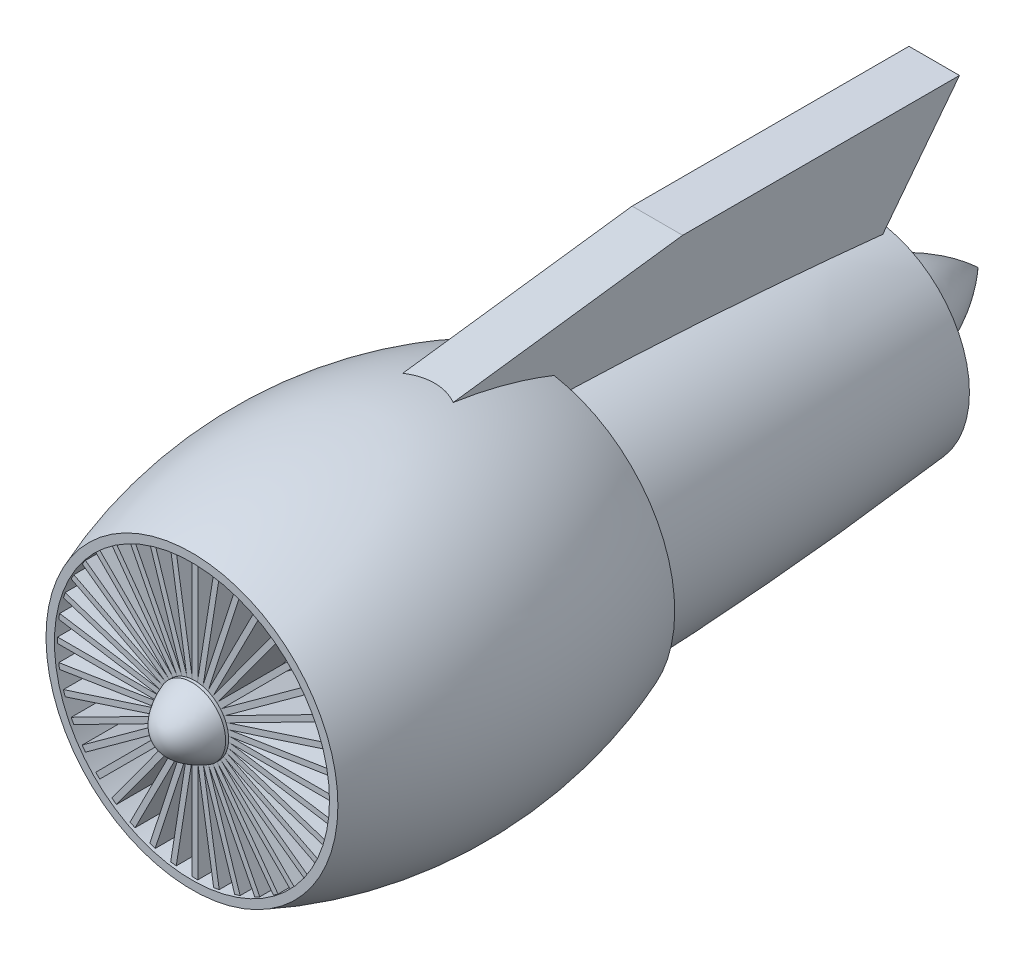
SolidWorks part; units mm, degrees
ref_plane "Front Plane" through (0, 0, 0) normal (0, 0, 1) x (1, 0, 0)
ref_plane "Top Plane" through (0, 0, 0) normal (0, 1, 0) x (1, 0, 0)
ref_plane "Right Plane" through (0, 0, 0) normal (1, 0, 0) x (0, 0, -1)
sketch "Sketch2" plane through (0, 0, 0) normal (1, 0, 0) x (0, 0, -1)
  line L0 (0, 0) -> (7418.07, 0) construction
  line L1 (304.8, 0) -> (304.8, 1320.8)
  line L2 (0, 1606.55) -> (7418.07, 1606.55) construction
  line L3 (0, 1606.55) -> (0, -1606.55) construction
  line L4 (0, -1606.55) -> (7418.07, -1606.55) construction
  line L5 (7418.07, 1606.55) -> (7418.07, -1606.55) construction
  line L6 (3352.8, 0) -> (3352.8, 1320.8)
  line L7 (6400.8, 0) -> (6400.8, 939.8)
  line L8 (0, 0) -> (7418.07, 0)
  arc A0 (304.8, 1320.8) -> (3352.8, 1320.8) centre (1828.8, -2600.325) cw
  arc A1 (3352.8, 1143) -> (6400.8, 939.8) centre (2010.8023, -41948.565) cw
  arc A2 (6400.8, 469.9) -> (7418.07, 0) centre (6186.9994, -1329.0255) cw
  spline S0 degree 3 poles (304.8, 304.8) (224.0091, 277.1634) (0, 180.4453) (0, 0) knots 0 0 0 0 1 1 1 1
  point P7 (0, 0)
  dimension "D10" = 43112.4568
  dimension "D11" = 1811.586
  dimension "D1" = 7418.07
  dimension "D2" = 3213.1
  dimension "D3" = 304.8
  dimension "D4" = 304.8
  dimension "D5" = 1320.8
  dimension "D6" = 3048
  dimension "D7" = 3048
  dimension "D8" = 177.8
  dimension "D9" = 203.2
revolve "Revolve3" add sketch "Sketch2" angle 360 about L0
sketch "Sketch3" plane through (0, 0, -304.8) normal (0, 0, 1) x (1, 0, 0)
  circle A0 centre (0, 0) radius 1244.6
  circle A1 centre (0, 0) radius 304.8
  circle A2 centre (0, 0) radius 304.8 construction
  circle A3 centre (0, 0) radius 1320.8 construction
  dimension "D1" = 76.2
extrude "Cut-Extrude1" cut sketch "Sketch3" against normal blind 609.6
sketch "Sketch4" plane through (0, 0, -6400.8) normal (0, 0, -1) x (-1, 0, 0)
  circle A0 centre (0, 0) radius 469.9
  circle A1 centre (0, 0) radius 469.9 construction
  circle A2 centre (0, 0) radius 914.4
  circle A3 centre (0, 0) radius 939.8 construction
  dimension "D1" = 25.4
extrude "Cut-Extrude4" cut sketch "Sketch4" against normal blind 914.4
sketch "Sketch5" plane through (0, 0, 0) normal (1, 0, 0) x (0, 0, -1)
  line L0 (1777.5046, 1457.7467) -> (4516.6379, 1817.1065)
  line L1 (4516.6379, 1817.1065) -> (7021.9455, 1817.1065)
  line L2 (7021.9455, 1817.1065) -> (6300.0388, 883.2967)
  line L3 (6300.0388, 883.2967) -> (3352.8, 1032.7016)
  line L4 (3352.8, -1320.8) -> (3352.8, 1320.8) construction
  line L5 (3352.8, 1032.7016) -> (1777.5046, 1457.7467)
extrude "Boss-Extrude1" add sketch "Sketch5" along normal mid plane 457.2
sketch "Sketch6" plane through (0, 0, -914.4) normal (0, 0, 1) x (1, 0, 0)
  line L0 (0, 0) -> (0, 1320.8) construction
  line L1 (-25.4, 1244.3408) -> (25.4, 1244.3408)
  line L2 (-25.4, 1244.3408) -> (-25.4, 0)
  line L3 (-25.4, 0) -> (25.4, 0)
  line L4 (25.4, 1244.3408) -> (25.4, 0)
  circle A0 centre (0, 0) radius 1244.6 construction
  point P6 (0, 1244.3408)
  dimension "D1" = 50.8
extrude "Boss-Extrude4" add sketch "Sketch6" along normal blind 582.422 separate body
pattern_circular "CirPattern2" count 40 over 360 about axis through (0, 0, 0) along (0, 0, 1)
